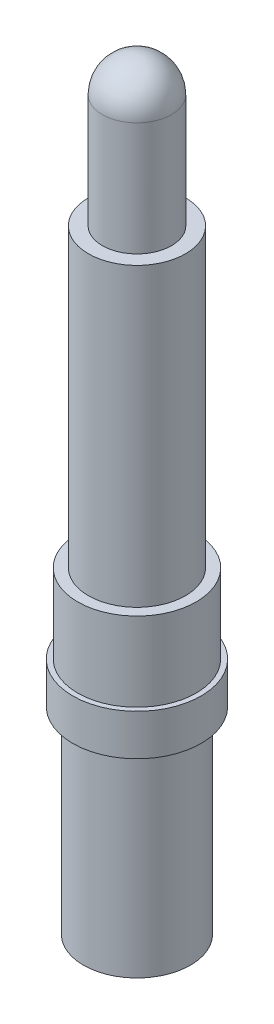
SolidWorks part; units mm, degrees
ref_plane "Front Plane" through (0, 0, 0) normal (0, 0, 1) x (1, 0, 0)
ref_plane "Top Plane" through (0, 0, 0) normal (0, 1, 0) x (1, 0, 0)
ref_plane "Right Plane" through (0, 0, 0) normal (1, 0, 0) x (0, 0, -1)
sketch "Sketch2" plane through (0, 0, 0) normal (0, 0, 1) x (1, 0, 0)
  line L0 (0, 0) -> (0, 11.2268) construction
  line L1 (0.5334, 11.2268) -> (0.5334, 9.4742)
  line L2 (0.5334, 9.4742) -> (0.7493, 9.4742)
  line L3 (0.7493, 9.4742) -> (0.7493, 4.9022)
  line L4 (0.7493, 4.9022) -> (0.9144, 4.9022)
  line L5 (0.9144, 4.9022) -> (0.9144, 3.683)
  line L6 (0.9144, 3.683) -> (0.9906, 3.683)
  line L7 (0.9906, 3.683) -> (0.9906, 3.048)
  line L8 (0.9906, 3.048) -> (0.8255, 3.048)
  line L9 (0.8255, 3.048) -> (0.8255, 0)
  line L10 (0.8255, 0) -> (0, 0)
  line L11 (0, 0) -> (0, 11.7602)
  line L12 (0, 0) -> (0, -5.7752) construction
  arc A0 (0, 11.7602) -> (0.5334, 11.2268) centre (0, 11.2268) cw
  dimension "D1" = 1.0668
  dimension "D2" = 1.9812
  dimension "D3" = 1.8288
  dimension "D4" = 1.4986
  dimension "D5" = 2.286
  dimension "D6" = 1.651
  dimension "D7" = 6.4262
  dimension "D8" = 0.635
  dimension "D9" = 4.572
  dimension "D10" = 3.048
revolve "Revolve1" add sketch "Sketch2" angle 360 about L12
ref_point "Point1"
